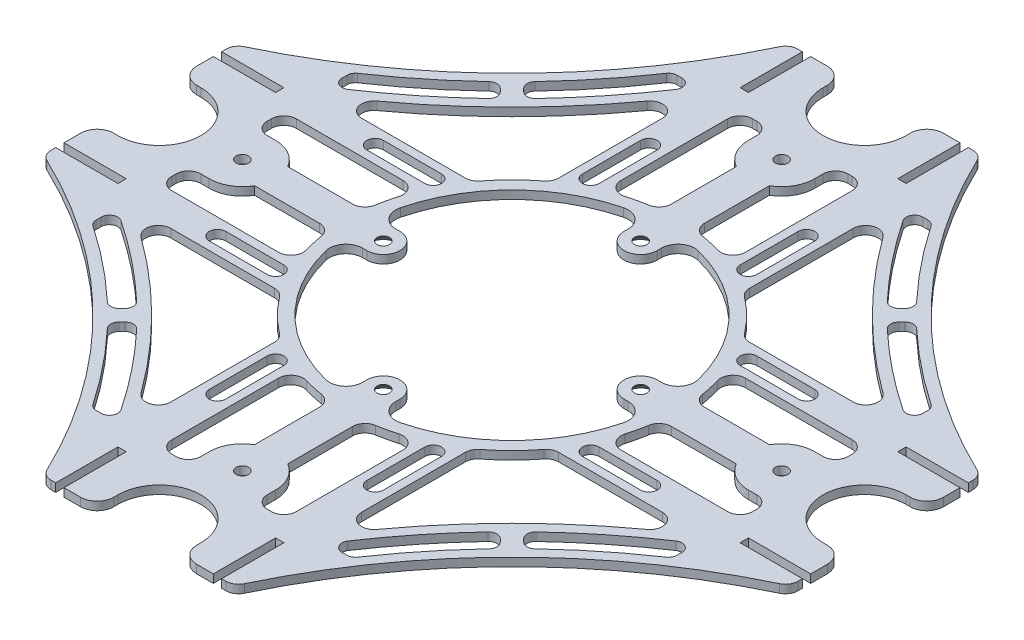
SolidWorks part; units mm, degrees
ref_plane "Front Plane" through (0, 0, 0) normal (0, 0, 1) x (1, 0, 0)
ref_plane "Top Plane" through (0, 0, 0) normal (0, 1, 0) x (1, 0, 0)
ref_plane "Right Plane" through (0, 0, 0) normal (1, 0, 0) x (0, 0, -1)
sketch "Sketch1" plane through (0, 0, 0) normal (0, 1, 0) x (1, 0, 0)
  line L0 (0, 100) -> (0, 0) construction
  line L1 (0, 0) -> (120.2145, 0) construction
  line L2 (4, 31) -> (4, 32.0156)
  line L3 (-4, 31) -> (-4, 32.0156)
  line L4 (-21.0921, 90) -> (-20, 90)
  line L5 (31, -4) -> (32.0156, -4)
  line L6 (31, 4) -> (32.0156, 4)
  line L7 (90, 21.0921) -> (90, 20)
  line L8 (0, 0) -> (163.4634, 163.4634) construction
  line L9 (-4, -31) -> (-4, -32.0156)
  line L10 (4, -31) -> (4, -32.0156)
  line L11 (21.0921, -90) -> (20, -90)
  line L12 (-31, 4) -> (-32.0156, 4)
  line L13 (-31, -4) -> (-32.0156, -4)
  line L14 (-90, -21.0921) -> (-90, -20)
  line L15 (-10, 85) -> (-10, 86)
  line L16 (10, 85) -> (10, 86)
  line L17 (85, 10) -> (86, 10)
  line L18 (85, -10) -> (86, -10)
  line L19 (10, -85) -> (10, -86)
  line L20 (-10, -85) -> (-10, -86)
  line L21 (-85, -10) -> (-86, -10)
  line L22 (-85, 10) -> (-86, 10)
  line L23 (14, 90) -> (18, 90)
  line L24 (-90, 14) -> (-90, 18)
  line L25 (90, -14) -> (90, -18)
  line L26 (-14, -90) -> (-18, -90)
  line L27 (20, 90) -> (20, 75)
  line L28 (20, 75) -> (18, 75)
  line L29 (18, 75) -> (18, 90)
  line L30 (-20, 90) -> (-20, 75)
  line L31 (-20, 75) -> (-18, 75)
  line L32 (-18, 75) -> (-18, 90)
  line L33 (90, 20) -> (75, 20)
  line L34 (75, 18) -> (90, 18)
  line L35 (75, 20) -> (75, 18)
  line L36 (75, -20) -> (75, -18)
  line L37 (90, -20) -> (75, -20)
  line L38 (75, -18) -> (90, -18)
  line L39 (20, -90) -> (20, -75)
  line L40 (18, -75) -> (18, -90)
  line L41 (20, -75) -> (18, -75)
  line L42 (-20, -75) -> (-18, -75)
  line L43 (-20, -90) -> (-20, -75)
  line L44 (-18, -75) -> (-18, -90)
  line L45 (-90, -20) -> (-75, -20)
  line L46 (-75, -18) -> (-90, -18)
  line L47 (-75, -20) -> (-75, -18)
  line L48 (-75, 20) -> (-75, 18)
  line L49 (-90, 20) -> (-75, 20)
  line L50 (-75, 18) -> (-90, 18)
  line L51 (-18, 90) -> (-14, 90)
  line L52 (20, 90) -> (21.0921, 90)
  line L53 (-90, 20) -> (-90, 21.0921)
  line L54 (-90, -18) -> (-90, -14)
  line L55 (-20, -90) -> (-21.0921, -90)
  line L56 (18, -90) -> (14, -90)
  line L57 (90, 18) -> (90, 14)
  line L58 (90, -20) -> (90, -21.0921)
  line L59 (-4, 58.0718) -> (-4, 42.4264)
  line L60 (4, 58.0718) -> (4, 42.4264)
  line L61 (-15, 41.2916) -> (-15, 67)
  line L62 (15, 41.2916) -> (15, 67)
  line L63 (-12, 70) -> (-11, 70)
  line L64 (-8, 65) -> (-8, 67)
  line L65 (8, 65) -> (8, 67)
  line L66 (11, 70) -> (12, 70)
  line L67 (41.2916, 15) -> (67, 15)
  line L68 (58.0718, 4) -> (42.4264, 4)
  line L69 (58.0718, -4) -> (42.4264, -4)
  line L70 (41.2916, -15) -> (67, -15)
  line L71 (70, -11) -> (70, -12)
  line L72 (65, -8) -> (67, -8)
  line L73 (65, 8) -> (67, 8)
  line L74 (70, 12) -> (70, 11)
  line L75 (15, -41.2916) -> (15, -67)
  line L76 (4, -58.0718) -> (4, -42.4264)
  line L77 (-4, -58.0718) -> (-4, -42.4264)
  line L78 (-15, -41.2916) -> (-15, -67)
  line L79 (-11, -70) -> (-12, -70)
  line L80 (-8, -65) -> (-8, -67)
  line L81 (8, -65) -> (8, -67)
  line L82 (12, -70) -> (11, -70)
  line L83 (-41.2916, -15) -> (-67, -15)
  line L84 (-58.0718, -4) -> (-42.4264, -4)
  line L85 (-58.0718, 4) -> (-42.4264, 4)
  line L86 (-41.2916, 15) -> (-67, 15)
  line L87 (-70, 11) -> (-70, 12)
  line L88 (-65, 8) -> (-67, 8)
  line L89 (-65, -8) -> (-67, -8)
  line L90 (-70, -12) -> (-70, -11)
  line L91 (-23, 34.2491) -> (-23, 59.2453)
  line L92 (23, 34.2491) -> (23, 59.2453)
  line L93 (34.2491, 23) -> (59.2453, 23)
  line L94 (34.2491, -23) -> (59.2453, -23)
  line L95 (23, -34.2491) -> (23, -59.2453)
  line L96 (-23, -34.2491) -> (-23, -59.2453)
  line L97 (-34.2491, -23) -> (-59.2453, -23)
  line L98 (-34.2491, 23) -> (-59.2453, 23)
  line L99 (-19, 52) -> (-19, 38) construction
  line L100 (-17, 52) -> (-17, 38)
  line L101 (-21, 52) -> (-21, 38)
  line L102 (19, 52) -> (19, 38) construction
  line L103 (17, 52) -> (17, 38)
  line L104 (21, 52) -> (21, 38)
  line L105 (52, 19) -> (38, 19) construction
  line L106 (52, 17) -> (38, 17)
  line L107 (52, 21) -> (38, 21)
  line L108 (52, -19) -> (38, -19) construction
  line L109 (52, -17) -> (38, -17)
  line L110 (52, -21) -> (38, -21)
  line L111 (19, -52) -> (19, -38) construction
  line L112 (17, -52) -> (17, -38)
  line L113 (21, -52) -> (21, -38)
  line L114 (-19, -52) -> (-19, -38) construction
  line L115 (-17, -52) -> (-17, -38)
  line L116 (-21, -52) -> (-21, -38)
  line L117 (-52, -19) -> (-38, -19) construction
  line L118 (-52, -17) -> (-38, -17)
  line L119 (-52, -21) -> (-38, -21)
  line L120 (-52, 19) -> (-38, 19) construction
  line L121 (-52, 17) -> (-38, 17)
  line L122 (-52, 21) -> (-38, 21)
  line L123 (70, -29.0377) -> (70, -30.2432)
  line L124 (48.0649, 45.2365) -> (48.7723, 45.9439)
  line L125 (45.2365, 48.0649) -> (45.9439, 48.7723)
  line L126 (29.0377, 70) -> (30.2432, 70)
  line L127 (70, 29.0377) -> (70, 30.2432)
  line L128 (48.0649, -45.2365) -> (48.7723, -45.9439)
  line L129 (45.2365, -48.0649) -> (45.9439, -48.7723)
  line L130 (29.0377, -70) -> (30.2432, -70)
  line L131 (-29.0377, -70) -> (-30.2432, -70)
  line L132 (-45.2365, -48.0649) -> (-45.9439, -48.7723)
  line L133 (-48.0649, -45.2365) -> (-48.7723, -45.9439)
  line L134 (-70, -29.0377) -> (-70, -30.2432)
  line L135 (-70, 29.0377) -> (-70, 30.2432)
  line L136 (-48.0649, 45.2365) -> (-48.7723, 45.9439)
  line L137 (-45.2365, 48.0649) -> (-45.9439, 48.7723)
  line L138 (-29.0377, 70) -> (-30.2432, 70)
  arc A0 (-8.9697, 35.8963) -> (-35.8963, 8.9697) centre (0, 0) ccw
  circle A1 centre (0, 31) radius 1.5
  arc A2 (-4, 31) -> (4, 31) centre (0, 31) ccw
  arc A3 (-10, 85) -> (10, 85) centre (0, 85) ccw
  arc A4 (-8, 65) -> (-4, 58.0718) centre (0, 65) ccw
  circle A5 centre (0, 65) radius 1.5
  arc A6 (85, 10) -> (85, -10) centre (85, 0) ccw
  arc A7 (65, 8) -> (58.0718, 4) centre (65, 0) ccw
  arc A8 (31, 4) -> (31, -4) centre (31, 0) ccw
  circle A9 centre (65, 0) radius 1.5
  circle A10 centre (31, 0) radius 1.5
  arc A11 (23.8002, 88.2908) -> (88.2908, 23.8002) centre (147.02, 147.02) ccw
  arc A12 (88.2908, -23.8002) -> (23.8002, -88.2908) centre (147.02, -147.02) ccw
  arc A13 (10, -85) -> (-10, -85) centre (0, -85) ccw
  arc A14 (-4, -58.0718) -> (-8, -65) centre (0, -65) ccw
  arc A15 (4, -31) -> (-4, -31) centre (0, -31) ccw
  circle A16 centre (0, -65) radius 1.5
  circle A17 centre (0, -31) radius 1.5
  arc A18 (-23.8002, -88.2908) -> (-88.2908, -23.8002) centre (-147.02, -147.02) ccw
  arc A19 (-85, -10) -> (-85, 10) centre (-85, 0) ccw
  arc A20 (-65, -8) -> (-58.0718, -4) centre (-65, 0) ccw
  arc A21 (-31, -4) -> (-31, 4) centre (-31, 0) ccw
  circle A22 centre (-65, 0) radius 1.5
  circle A23 centre (-31, 0) radius 1.5
  arc A24 (-88.2908, 23.8002) -> (-23.8002, 88.2908) centre (-147.02, 147.02) ccw
  arc A25 (8.9697, -35.8963) -> (35.8963, -8.9697) centre (0, 0) ccw
  arc A26 (-35.8963, -8.9697) -> (-8.9697, -35.8963) centre (0, 0) ccw
  arc A27 (35.8963, 8.9697) -> (8.9697, 35.8963) centre (0, 0) ccw
  arc A28 (-6.5116, 39.4664) -> (-11.1628, 38.4108) centre (0, 0) ccw
  arc A29 (-4, -32.0156) -> (-8.9697, -35.8963) centre (-8, -32.0156) cw
  arc A30 (4, -32.0156) -> (8.9697, -35.8963) centre (8, -32.0156) ccw
  arc A31 (32.0156, -4) -> (35.8963, -8.9697) centre (32.0156, -8) cw
  arc A32 (32.0156, 4) -> (35.8963, 8.9697) centre (32.0156, 8) ccw
  arc A33 (-32.0156, -4) -> (-35.8963, -8.9697) centre (-32.0156, -8) ccw
  arc A34 (-32.0156, 4) -> (-35.8963, 8.9697) centre (-32.0156, 8) cw
  arc A35 (4, 32.0156) -> (8.9697, 35.8963) centre (8, 32.0156) cw
  arc A36 (-4, 32.0156) -> (-8.9697, 35.8963) centre (-8, 32.0156) ccw
  arc A37 (-21.0921, -90) -> (-23.8002, -88.2908) centre (-21.0921, -87) cw
  arc A38 (23.8002, -88.2908) -> (21.0921, -90) centre (21.0921, -87) cw
  arc A39 (90, -21.0921) -> (88.2908, -23.8002) centre (87, -21.0921) cw
  arc A40 (90, 21.0921) -> (88.2908, 23.8002) centre (87, 21.0921) ccw
  arc A41 (23.8002, 88.2908) -> (21.0921, 90) centre (21.0921, 87) ccw
  arc A42 (-21.0921, 90) -> (-23.8002, 88.2908) centre (-21.0921, 87) ccw
  arc A43 (-90, 21.0921) -> (-88.2908, 23.8002) centre (-87, 21.0921) cw
  arc A44 (-88.2908, -23.8002) -> (-90, -21.0921) centre (-87, -21.0921) cw
  arc A45 (-86, 10) -> (-90, 14) centre (-86, 14) cw
  arc A46 (-86, -10) -> (-90, -14) centre (-86, -14) ccw
  arc A47 (-10, -86) -> (-14, -90) centre (-14, -86) cw
  arc A48 (10, -86) -> (14, -90) centre (14, -86) ccw
  arc A49 (86, -10) -> (90, -14) centre (86, -14) cw
  arc A50 (86, 10) -> (90, 14) centre (86, 14) ccw
  arc A51 (10, 86) -> (14, 90) centre (14, 86) cw
  arc A52 (-10, 86) -> (-14, 90) centre (-14, 86) ccw
  arc A53 (4, 58.0718) -> (8, 65) centre (0, 65) ccw
  arc A54 (58.0718, -4) -> (65, -8) centre (65, 0) ccw
  arc A55 (39.4664, 6.5116) -> (38.4108, 11.1628) centre (0, 0) ccw
  arc A56 (6.5116, -39.4664) -> (11.1628, -38.4108) centre (0, 0) ccw
  arc A57 (8, -65) -> (4, -58.0718) centre (0, -65) ccw
  arc A58 (-58.0718, 4) -> (-65, 8) centre (-65, 0) ccw
  arc A59 (-39.4664, -6.5116) -> (-38.4108, -11.1628) centre (0, 0) ccw
  arc A60 (28.4285, 61.0067) -> (61.0067, 28.4285) centre (147.02, 147.02) ccw
  arc A61 (61.0067, -28.4285) -> (28.4285, -61.0067) centre (147.02, -147.02) ccw
  arc A62 (14.7731, 83.9882) -> (83.9882, 14.7731) centre (147.02, 147.02) ccw construction
  arc A63 (-28.4285, -61.0067) -> (-61.0067, -28.4285) centre (-147.02, -147.02) ccw
  arc A64 (-61.0067, 28.4285) -> (-28.4285, 61.0067) centre (-147.02, 147.02) ccw
  arc A65 (-11.1628, -38.4108) -> (-6.5116, -39.4664) centre (0, 0) ccw
  arc A66 (24.186, -31.8596) -> (31.8596, -24.186) centre (0, 0) ccw
  arc A67 (38.4108, -11.1628) -> (39.4664, -6.5116) centre (0, 0) ccw
  arc A68 (31.8596, 24.186) -> (24.186, 31.8596) centre (0, 0) ccw
  arc A69 (11.1628, 38.4108) -> (6.5116, 39.4664) centre (0, 0) ccw
  arc A70 (-24.186, 31.8596) -> (-31.8596, 24.186) centre (0, 0) ccw
  arc A71 (-38.4108, 11.1628) -> (-39.4664, 6.5116) centre (0, 0) ccw
  arc A72 (-31.8596, -24.186) -> (-24.186, -31.8596) centre (0, 0) ccw
  arc A73 (61.0067, 28.4285) -> (59.2453, 23) centre (59.2453, 26) cw
  arc A74 (34.2491, 23) -> (31.8596, 24.186) centre (34.2491, 26) cw
  arc A75 (23, 34.2491) -> (24.186, 31.8596) centre (26, 34.2491) ccw
  arc A76 (28.4285, 61.0067) -> (23, 59.2453) centre (26, 59.2453) ccw
  arc A77 (-28.4285, 61.0067) -> (-23, 59.2453) centre (-26, 59.2453) cw
  arc A78 (-61.0067, 28.4285) -> (-59.2453, 23) centre (-59.2453, 26) ccw
  arc A79 (-34.2491, 23) -> (-31.8596, 24.186) centre (-34.2491, 26) ccw
  arc A80 (-23, 34.2491) -> (-24.186, 31.8596) centre (-26, 34.2491) cw
  arc A81 (61.0067, -28.4285) -> (59.2453, -23) centre (59.2453, -26) ccw
  arc A82 (34.2491, -23) -> (31.8596, -24.186) centre (34.2491, -26) ccw
  arc A83 (23, -34.2491) -> (24.186, -31.8596) centre (26, -34.2491) cw
  arc A84 (23, -59.2453) -> (28.4285, -61.0067) centre (26, -59.2453) ccw
  arc A85 (-28.4285, -61.0067) -> (-23, -59.2453) centre (-26, -59.2453) ccw
  arc A86 (-23, -34.2491) -> (-24.186, -31.8596) centre (-26, -34.2491) ccw
  arc A87 (-34.2491, -23) -> (-31.8596, -24.186) centre (-34.2491, -26) cw
  arc A88 (-61.0067, -28.4285) -> (-59.2453, -23) centre (-59.2453, -26) cw
  arc A89 (-15, -41.2916) -> (-11.1628, -38.4108) centre (-12, -41.2916) cw
  arc A90 (-4, -42.4264) -> (-6.5116, -39.4664) centre (-7, -42.4264) ccw
  arc A91 (4, -42.4264) -> (6.5116, -39.4664) centre (7, -42.4264) cw
  arc A92 (15, -41.2916) -> (11.1628, -38.4108) centre (12, -41.2916) ccw
  arc A93 (15, -67) -> (12, -70) centre (12, -67) cw
  arc A94 (8, -67) -> (11, -70) centre (11, -67) ccw
  arc A95 (-11, -70) -> (-8, -67) centre (-11, -67) ccw
  arc A96 (-15, -67) -> (-12, -70) centre (-12, -67) ccw
  arc A97 (67, 8) -> (70, 11) centre (67, 11) ccw
  arc A98 (67, 15) -> (70, 12) centre (67, 12) cw
  arc A99 (42.4264, 4) -> (39.4664, 6.5116) centre (42.4264, 7) cw
  arc A100 (42.4264, -4) -> (39.4664, -6.5116) centre (42.4264, -7) ccw
  arc A101 (70, -11) -> (67, -8) centre (67, -11) ccw
  arc A102 (67, -15) -> (70, -12) centre (67, -12) ccw
  arc A103 (41.2916, -15) -> (38.4108, -11.1628) centre (41.2916, -12) cw
  arc A104 (41.2916, 15) -> (38.4108, 11.1628) centre (41.2916, 12) ccw
  arc A105 (-12, 70) -> (-15, 67) centre (-12, 67) ccw
  arc A106 (-8, 67) -> (-11, 70) centre (-11, 67) ccw
  arc A107 (8, 67) -> (11, 70) centre (11, 67) cw
  arc A108 (15, 67) -> (12, 70) centre (12, 67) ccw
  arc A109 (15, 41.2916) -> (11.1628, 38.4108) centre (12, 41.2916) cw
  arc A110 (4, 42.4264) -> (6.5116, 39.4664) centre (7, 42.4264) ccw
  arc A111 (-4, 42.4264) -> (-6.5116, 39.4664) centre (-7, 42.4264) cw
  arc A112 (-15, 41.2916) -> (-11.1628, 38.4108) centre (-12, 41.2916) ccw
  arc A113 (-42.4264, -4) -> (-39.4664, -6.5116) centre (-42.4264, -7) cw
  arc A114 (-41.2916, -15) -> (-38.4108, -11.1628) centre (-41.2916, -12) ccw
  arc A115 (-67, -15) -> (-70, -12) centre (-67, -12) cw
  arc A116 (-67, -8) -> (-70, -11) centre (-67, -11) ccw
  arc A117 (-70, 11) -> (-67, 8) centre (-67, 11) ccw
  arc A118 (-42.4264, 4) -> (-39.4664, 6.5116) centre (-42.4264, 7) ccw
  arc A119 (-41.2916, 15) -> (-38.4108, 11.1628) centre (-41.2916, 12) cw
  arc A120 (-67, 15) -> (-70, 12) centre (-67, 12) ccw
  arc A121 (-17, 52) -> (-21, 52) centre (-19, 52) ccw
  arc A122 (-21, 38) -> (-17, 38) centre (-19, 38) ccw
  arc A123 (17, 52) -> (21, 52) centre (19, 52) cw
  arc A124 (21, 38) -> (17, 38) centre (19, 38) cw
  arc A125 (52, 17) -> (52, 21) centre (52, 19) ccw
  arc A126 (38, 21) -> (38, 17) centre (38, 19) ccw
  arc A127 (52, -17) -> (52, -21) centre (52, -19) cw
  arc A128 (38, -21) -> (38, -17) centre (38, -19) cw
  arc A129 (17, -52) -> (21, -52) centre (19, -52) ccw
  arc A130 (21, -38) -> (17, -38) centre (19, -38) ccw
  arc A131 (-17, -52) -> (-21, -52) centre (-19, -52) cw
  arc A132 (-21, -38) -> (-17, -38) centre (-19, -38) cw
  arc A133 (-52, -17) -> (-52, -21) centre (-52, -19) ccw
  arc A134 (-38, -21) -> (-38, -17) centre (-38, -19) ccw
  arc A135 (-52, 17) -> (-52, 21) centre (-52, 19) cw
  arc A136 (-38, 21) -> (-38, 17) centre (-38, 19) cw
  arc A137 (31.8996, 69.1209) -> (45.9834, 51.56) centre (147.02, 147.02) ccw
  arc A138 (48.1053, 42.3688) -> (66.887, 27.3759) centre (147.02, 147.02) ccw
  arc A139 (27.3759, 66.887) -> (42.3688, 48.1053) centre (147.02, 147.02) ccw
  arc A140 (21.5434, 87.2151) -> (87.2151, 21.5434) centre (147.02, 147.02) ccw construction
  arc A141 (51.56, 45.9834) -> (69.1209, 31.8996) centre (147.02, 147.02) ccw
  arc A142 (66.887, -27.3759) -> (48.1053, -42.3688) centre (147.02, -147.02) ccw
  arc A143 (69.1209, -31.8996) -> (51.56, -45.9834) centre (147.02, -147.02) ccw
  arc A144 (45.9834, -51.56) -> (31.8996, -69.1209) centre (147.02, -147.02) ccw
  arc A145 (42.3688, -48.1053) -> (27.3759, -66.887) centre (147.02, -147.02) ccw
  arc A146 (-27.3759, -66.887) -> (-42.3688, -48.1053) centre (-147.02, -147.02) ccw
  arc A147 (-31.8996, -69.1209) -> (-45.9834, -51.56) centre (-147.02, -147.02) ccw
  arc A148 (-51.56, -45.9834) -> (-69.1209, -31.8996) centre (-147.02, -147.02) ccw
  arc A149 (-48.1053, -42.3688) -> (-66.887, -27.3759) centre (-147.02, -147.02) ccw
  arc A150 (-66.887, 27.3759) -> (-48.1053, 42.3688) centre (-147.02, 147.02) ccw
  arc A151 (-69.1209, 31.8996) -> (-51.56, 45.9834) centre (-147.02, 147.02) ccw
  arc A152 (-45.9834, 51.56) -> (-31.8996, 69.1209) centre (-147.02, 147.02) ccw
  arc A153 (-42.3688, 48.1053) -> (-27.3759, 66.887) centre (-147.02, 147.02) ccw
  arc A154 (70, -30.2432) -> (69.1209, -31.8996) centre (68, -30.2432) cw
  arc A155 (70, -29.0377) -> (66.887, -27.3759) centre (68, -29.0377) ccw
  arc A156 (48.1053, -42.3688) -> (48.0649, -45.2365) centre (49.4791, -43.8223) ccw
  arc A157 (51.56, -45.9834) -> (48.7723, -45.9439) centre (50.1865, -44.5297) cw
  arc A158 (45.2365, -48.0649) -> (42.3688, -48.1053) centre (43.8223, -49.4791) ccw
  arc A159 (45.9439, -48.7723) -> (45.9834, -51.56) centre (44.5297, -50.1865) cw
  arc A160 (31.8996, -69.1209) -> (30.2432, -70) centre (30.2432, -68) cw
  arc A161 (27.3759, -66.887) -> (29.0377, -70) centre (29.0377, -68) ccw
  arc A162 (-29.0377, -70) -> (-27.3759, -66.887) centre (-29.0377, -68) ccw
  arc A163 (-30.2432, -70) -> (-31.8996, -69.1209) centre (-30.2432, -68) cw
  arc A164 (-45.9834, -51.56) -> (-45.9439, -48.7723) centre (-44.5297, -50.1865) cw
  arc A165 (-42.3688, -48.1053) -> (-45.2365, -48.0649) centre (-43.8223, -49.4791) ccw
  arc A166 (-48.0649, -45.2365) -> (-48.1053, -42.3688) centre (-49.4791, -43.8223) ccw
  arc A167 (-48.7723, -45.9439) -> (-51.56, -45.9834) centre (-50.1865, -44.5297) cw
  arc A168 (-69.1209, -31.8996) -> (-70, -30.2432) centre (-68, -30.2432) cw
  arc A169 (-66.887, -27.3759) -> (-70, -29.0377) centre (-68, -29.0377) ccw
  arc A170 (-27.3759, 66.887) -> (-29.0377, 70) centre (-29.0377, 68) ccw
  arc A171 (-31.8996, 69.1209) -> (-30.2432, 70) centre (-30.2432, 68) cw
  arc A172 (-45.9439, 48.7723) -> (-45.9834, 51.56) centre (-44.5297, 50.1865) cw
  arc A173 (-45.2365, 48.0649) -> (-42.3688, 48.1053) centre (-43.8223, 49.4791) ccw
  arc A174 (-70, 29.0377) -> (-66.887, 27.3759) centre (-68, 29.0377) ccw
  arc A175 (-48.1053, 42.3688) -> (-48.0649, 45.2365) centre (-49.4791, 43.8223) ccw
  arc A176 (-51.56, 45.9834) -> (-48.7723, 45.9439) centre (-50.1865, 44.5297) cw
  arc A177 (-70, 30.2432) -> (-69.1209, 31.8996) centre (-68, 30.2432) cw
  arc A178 (66.887, 27.3759) -> (70, 29.0377) centre (68, 29.0377) ccw
  arc A179 (69.1209, 31.8996) -> (70, 30.2432) centre (68, 30.2432) cw
  arc A180 (48.0649, 45.2365) -> (48.1053, 42.3688) centre (49.4791, 43.8223) ccw
  arc A181 (48.7723, 45.9439) -> (51.56, 45.9834) centre (50.1865, 44.5297) cw
  arc A182 (45.2365, 48.0649) -> (42.3688, 48.1053) centre (43.8223, 49.4791) cw
  arc A183 (45.9439, 48.7723) -> (45.9834, 51.56) centre (44.5297, 50.1865) ccw
  arc A184 (31.8996, 69.1209) -> (30.2432, 70) centre (30.2432, 68) ccw
  arc A185 (27.3759, 66.887) -> (29.0377, 70) centre (29.0377, 68) cw
  point P73 (0, 0)
  point P90 (0, 0)
  point P110 (0, 0)
  point P133 (90, 23)
  point P136 (23, 90)
  point P157 (10, 90)
  point P211 (0, 0)
  point P225 (23, 32.7261)
  point P237 (0, 0)
  point P244 (-23, 32.7261)
  point P299 (8, 70)
  point P304 (15, 37.081)
  point P329 (-19, 45)
  point P336 (19, 45)
  point P346 (45, 19)
  point P353 (45, -19)
  point P360 (19, -45)
  point P367 (-19, -45)
  point P374 (-45, -19)
  point P381 (-45, 19)
  point P386 (0, 0)
  point P388 (17.0299, 85.0639)
  point P389 (85.0639, 17.0299)
  point P394 (45.9142, 43.0858)
  point P395 (50.9142, 48.0858)
  point P396 (43.0858, 45.9142)
  point P397 (48.0858, 50.9142)
  point P435 (0, 0)
  point P487 (46.6207, 43.7923)
  point P490 (50.1566, 47.3281)
  dimension "D1" = 273
  dimension "D5" = 4
  dimension "D6" = 3
  dimension "D7" = 4
  dimension "D11" = 3
  dimension "D12" = 3
  dimension "D14" = 2
  dimension "D19" = 2
  dimension "D20" = 3
  dimension "D21" = 3
  dimension "D13" = 14
  dimension "D15" = 7
  dimension "D9" = 10
  dimension "D17" = 2.5
  dimension "D18" = 4
  dimension "D2" = 4
  dimension "D3" = 4
  dimension "D4" = 4
  dimension "D8" = 4
  dimension "D10" = 4
  dimension "D16" = 4
extrude "Boss-Extrude1" add sketch "Sketch1" along normal blind 2
chamfer "Chamfer1" distance 1.75 angle 45 4 edges at (-31, 0, 1.5) (0, 0, -29.5) (31, 0, 1.5) (0, 0, 32.5)
